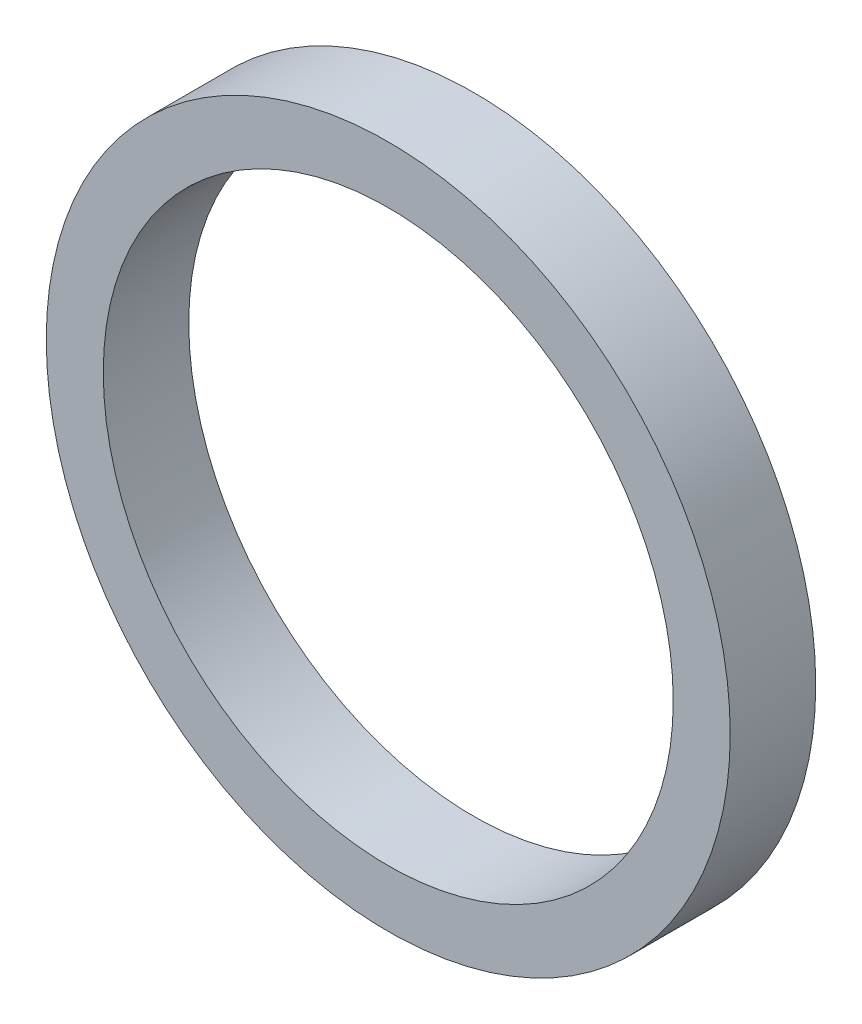
SolidWorks part; units mm, degrees
ref_plane "Front Plane" through (0, 0, 0) normal (0, 0, 1) x (1, 0, 0)
ref_plane "Top Plane" through (0, 0, 0) normal (0, 1, 0) x (1, 0, 0)
ref_plane "Right Plane" through (0, 0, 0) normal (1, 0, 0) x (0, 0, -1)
sketch "Sketch1" plane through (0, 0, 0) normal (0, 0, 1) x (1, 0, 0)
  circle A0 centre (0, 0) radius 240
extrude "Boss-Extrude1" add sketch "Sketch1" along normal blind 60
sketch "Sketch2" plane through (0, 0, 60) normal (0, 0, 1) x (1, 0, 0)
  circle A0 centre (0, 0) radius 200
extrude "Cut-Extrude1" cut sketch "Sketch2" against normal blind 60
